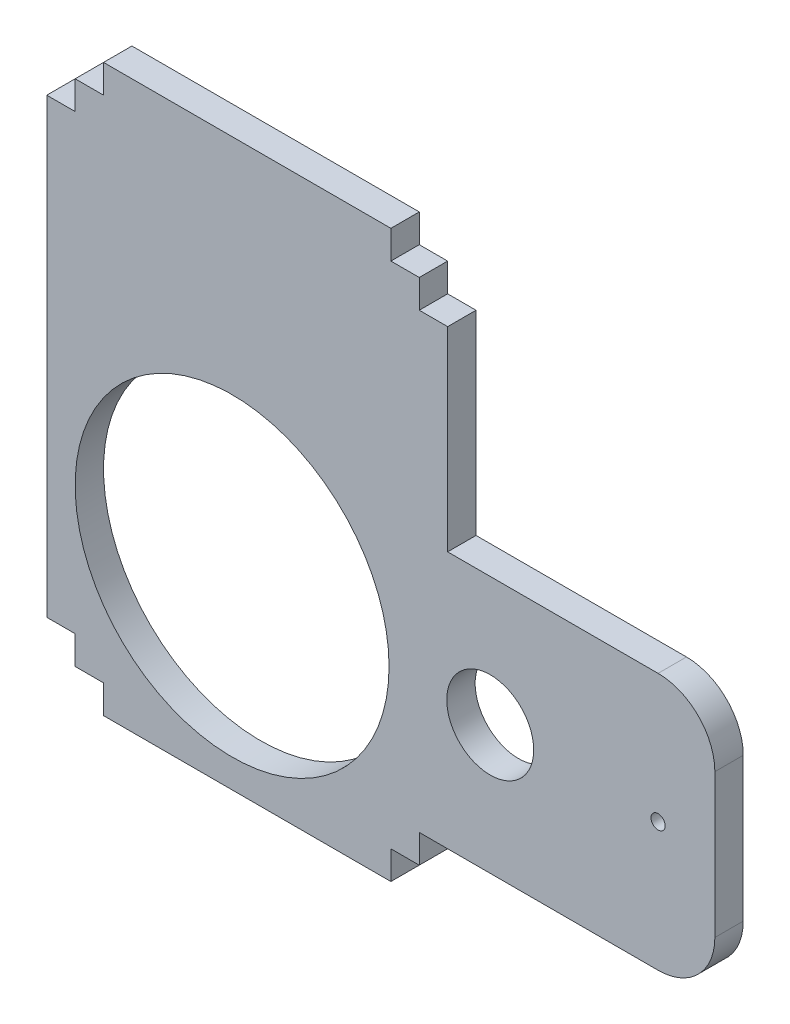
SolidWorks part; units mm, degrees
material "Acrylic (Medium-high impact)"
ref_plane "Front Plane" through (0, 0, 0) normal (0, 0, 1) x (1, 0, 0)
ref_plane "Top Plane" through (0, 0, 0) normal (0, 1, 0) x (1, 0, 0)
ref_plane "Right Plane" through (0, 0, 0) normal (1, 0, 0) x (0, 0, -1)
sketch "Sketch1" plane through (0, 0, 0) normal (0, 0, 1) x (1, 0, 0)
  line L1 (-35.1155, -35.1155) -> (-28.7655, -35.1155)
  line L2 (-35.1155, -35.1155) -> (-35.1155, -28.7655)
  line L3 (-35.1155, 78.7527) -> (-28.7655, 78.7527)
  line L4 (41.8719, -35.1155) -> (41.8719, -28.7655)
  line L6 (41.8719, 72.4027) -> (41.8719, 78.7527)
  line L7 (108.0008, -41.148) -> (108.0008, 111.379) construction
  line L8 (35.5219, -35.1155) -> (35.5219, -41.4655)
  line L9 (35.5219, -41.4655) -> (-28.7655, -41.4655)
  line L10 (-28.7655, -35.1155) -> (-28.7655, -41.4655)
  line L11 (-35.1155, -28.7655) -> (-41.4655, -28.7655)
  line L12 (35.5219, 78.7527) -> (41.8719, 78.7527)
  line L13 (-35.1155, 72.4027) -> (-41.4655, 72.4027)
  line L14 (-41.4655, -28.7655) -> (-41.4655, 72.4027)
  line L15 (9.1821, 35.1155) -> (48.2219, 35.1155) construction
  line L16 (35.5219, 78.7527) -> (35.5219, 85.1027)
  line L17 (35.5219, 85.1027) -> (-28.7655, 85.1027)
  line L18 (-28.7655, 78.7527) -> (-28.7655, 85.1027)
  line L19 (41.8719, -28.7655) -> (95.3008, -28.7655)
  line L20 (35.5219, -35.1155) -> (41.8719, -35.1155)
  line L21 (48.2219, 28.7655) -> (95.3008, 28.7655)
  line L22 (108.0008, -16.0655) -> (108.0008, 16.0655)
  line L23 (-35.1155, 72.4027) -> (-35.1155, 78.7527)
  line L27 (41.8719, 72.4027) -> (48.2219, 72.4027)
  line L30 (48.2219, 72.4027) -> (48.2219, 28.7655)
  line L31 (48.2219, 75.5777) -> (9.1821, 75.5777) construction
  line L32 (48.2219, 85.1027) -> (48.2219, -41.4655) construction
  line L33 (108.0008, 0) -> (57.7469, 0) construction
  circle A0 centre (0, 0) radius 35.1155 construction
  circle A1 centre (0, 0) radius 35.1155
  circle A2 centre (57.7469, 0) radius 9.525 construction
  circle A3 centre (57.7469, 0) radius 9.525 construction
  circle A4 centre (57.7469, 0) radius 9.7234
  arc A5 (95.3008, 28.7655) -> (108.0008, 16.0655) centre (95.3008, 16.0655) cw
  arc A6 (95.3008, -28.7655) -> (108.0008, -16.0655) centre (95.3008, -16.0655) ccw
  circle A7 centre (95.3008, 0) radius 1.5875
  dimension "D6" = 12.7
  dimension "D7" = 3.175
  dimension "D8" = 12.7
  dimension "D1" = 6.35
  dimension "D2" = 6.35
  dimension "D3" = 6.35
  dimension "D4" = 3.175
  dimension "D5" = 0.1984
extrude "Boss-Extrude1" add sketch "Sketch1" against normal blind 6.35
